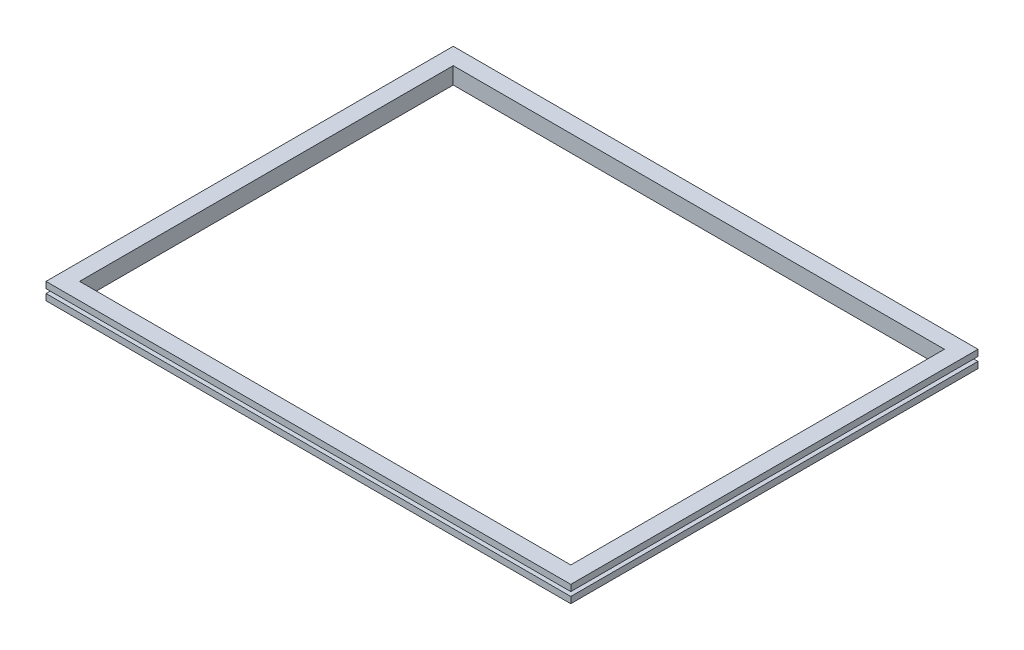
SolidWorks part; units mm, degrees
ref_plane "Front Plane" through (0, 0, 0) normal (0, 0, 1) x (1, 0, 0)
ref_plane "Top Plane" through (0, 0, 0) normal (0, 1, 0) x (1, 0, 0)
ref_plane "Right Plane" through (0, 0, 0) normal (1, 0, 0) x (0, 0, -1)
sketch "Sketch1" plane through (0, 0, 0) normal (0, 1, 0) x (1, 0, 0)
  line L1 (625, -485) -> (-625, -485)
  line L2 (625, -485) -> (625, 485)
  line L3 (625, 485) -> (-625, 485)
  line L4 (-625, -485) -> (-625, 485)
  line L5 (625, -485) -> (-625, 485) construction
  line L6 (625, 485) -> (-625, -485) construction
  line L7 (585, -445) -> (-585, -445)
  line L8 (585, -445) -> (585, 445)
  line L9 (585, 445) -> (-585, 445)
  line L10 (-585, -445) -> (-585, 445)
  line L11 (585, -445) -> (-585, 445) construction
  line L12 (585, 445) -> (-585, -445) construction
  point P0 (0, 0)
  point P6 (0, 0)
  dimension "D1" = 970
  dimension "D2" = 1250
  dimension "D3" = 40
  dimension "D4" = 40
extrude "Boss-Extrude1" add sketch "Sketch1" along normal blind 40
sketch "Sketch2" plane through (0, 0, 485) normal (0, 0, 1) x (1, 0, 0)
  line L0 (-625, 40) -> (-625, 0) construction
  line L1 (-625, 25) -> (-615, 25)
  line L2 (-625, 25) -> (-625, 15)
  line L3 (-625, 15) -> (-615, 15)
  line L4 (-615, 25) -> (-615, 15)
  line L5 (-625, 25) -> (-615, 15) construction
  line L6 (-625, 15) -> (-615, 25) construction
  line L7 (-625, 40) -> (625, 40) construction
  line L8 (615, 25) -> (625, 25)
  line L9 (615, 25) -> (615, 15)
  line L10 (615, 15) -> (625, 15)
  line L11 (625, 25) -> (625, 15)
  line L12 (625, 40) -> (625, 0) construction
  point P0 (-620, 20)
  point P14 (625, 20)
  dimension "D1" = 10
  dimension "D2" = 20
  dimension "D3" = 20
extrude "Cut-Extrude1" cut sketch "Sketch2" against normal through all both and the other way through all
sketch "Sketch3" plane through (-625, 0, 0) normal (-1, 0, 0) x (0, 0, 1)
  line L0 (-485, 40) -> (485, 40) construction
  line L1 (475, 25) -> (485, 25)
  line L2 (475, 25) -> (475, 15)
  line L3 (475, 15) -> (485, 15)
  line L4 (485, 25) -> (485, 15)
  line L5 (475, 25) -> (485, 15) construction
  line L6 (475, 15) -> (485, 25) construction
  line L7 (485, 25) -> (485, 15) construction
  line L8 (-485, 15) -> (-485, 25) construction
  line L9 (-475, 15) -> (-485, 15)
  line L10 (-475, 15) -> (-475, 25)
  line L11 (-475, 25) -> (-485, 25)
  line L12 (-485, 15) -> (-485, 25)
  line L13 (-475, 15) -> (-485, 25) construction
  line L14 (-475, 25) -> (-485, 15) construction
  point P0 (480, 20)
  point P10 (-480, 20)
  dimension "D1" = 10
  dimension "D2" = 10
  dimension "D3" = 20
  dimension "D4" = 10
  dimension "D5" = 10
  dimension "D6" = 20
extrude "Cut-Extrude2" cut sketch "Sketch3" against normal through all both
